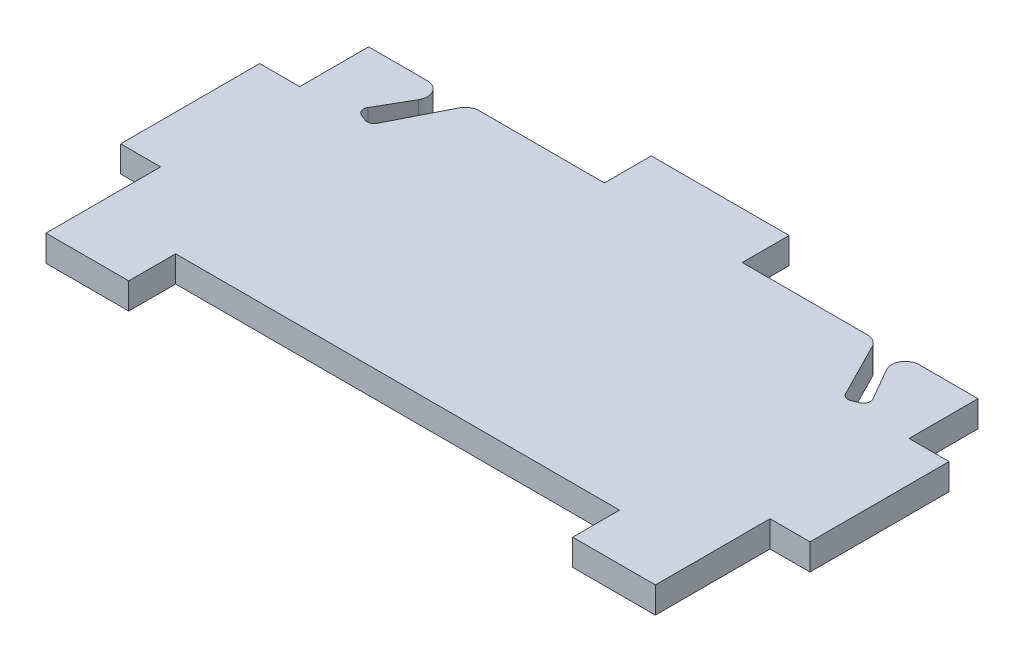
SolidWorks part; units mm, degrees
ref_plane "Front Plane" through (0, 0, 0) normal (0, 0, 1) x (1, 0, 0)
ref_plane "Top Plane" through (0, 0, 0) normal (0, 1, 0) x (1, 0, 0)
ref_plane "Right Plane" through (0, 0, 0) normal (1, 0, 0) x (0, 0, -1)
sketch "Sketch1" plane through (0, 0, 0) normal (0, 1, 0) x (1, 0, 0)
  line L0 (0, 29.083) -> (0, -47.5431) construction
  line L1 (-56.134, 29.083) -> (-40.894, 29.083)
  line L2 (-56.134, 29.083) -> (-56.134, 16.383)
  line L3 (-40.894, -21.717) -> (40.894, -21.717)
  line L4 (56.134, 29.083) -> (56.134, 16.383)
  line L5 (-56.134, 29.083) -> (56.134, -29.083) construction
  line L6 (-56.134, -29.083) -> (56.134, 29.083) construction
  line L7 (-56.134, 16.383) -> (-63.5, 16.383)
  line L9 (-56.134, -9.2306) -> (-63.5, -9.2306)
  line L10 (-63.5, 16.383) -> (-63.5, -9.2306)
  line L11 (56.134, -9.2306) -> (63.5, -9.2306)
  line L12 (63.5, 16.383) -> (63.5, -9.2306)
  line L13 (56.134, 16.383) -> (63.5, 16.383)
  line L14 (-56.134, -9.2306) -> (-56.134, -29.083)
  line L15 (56.134, -9.2306) -> (56.134, -29.083)
  line L16 (40.894, -21.717) -> (40.894, -30.353)
  line L18 (-56.134, -29.083) -> (-56.134, -30.353)
  line L19 (-56.134, -30.353) -> (-40.894, -30.353)
  line L20 (-40.894, -21.717) -> (-40.894, -30.353)
  line L21 (56.134, -30.353) -> (40.894, -30.353)
  line L22 (56.134, -29.083) -> (56.134, -30.353)
  line L23 (-37.338, 29.083) -> (-12.7, 29.083)
  line L29 (-40.894, 29.083) -> (-47.2419, 18.0833)
  line L30 (-47.2419, 18.0833) -> (-43.6859, 16.6246)
  line L31 (-37.338, 29.083) -> (-43.6859, 16.6246)
  line L32 (47.2419, 18.0833) -> (43.6859, 16.6246)
  line L33 (37.338, 29.083) -> (43.6859, 16.6246)
  line L34 (40.894, 29.083) -> (47.2419, 18.0833)
  line L35 (40.894, 29.083) -> (56.134, 29.083)
  line L36 (0, 37.719) -> (0, 26.6468) construction
  line L38 (-12.7, 29.083) -> (-12.7, 37.719)
  line L39 (-12.7, 37.719) -> (12.7, 37.719)
  line L40 (12.7, 29.083) -> (12.7, 37.719)
  line L41 (12.7, 29.083) -> (37.338, 29.083)
  point P0 (0, 0)
  dimension "D1" = 112.268
  dimension "D2" = 50.8
  dimension "D3" = 7.366
  dimension "D4" = 12.7
  dimension "D5" = 8.636
  dimension "D6" = 15.24
  dimension "D7" = 3.556
  dimension "D8" = 3.556
  dimension "D9" = 117
  dimension "D10" = 15.24
  dimension "D11" = 12.7
  dimension "D12" = 25.4
  dimension "D13" = 8.636
extrude "Boss-Extrude1" add sketch "Sketch1" along normal blind 4.826
fillet "Fillet1" radius 1.27 4 edges at (47.2419, 2.413, -18.0833) (43.6859, 2.413, -16.6246) (-43.6859, 2.413, -16.6246) (-47.2419, 2.413, -18.0833)
fillet "Fillet2" radius 2.54 4 edges at (37.338, 2.413, -29.083) (40.894, 2.413, -29.083) (-37.338, 2.413, -29.083) (-40.894, 2.413, -29.083)
